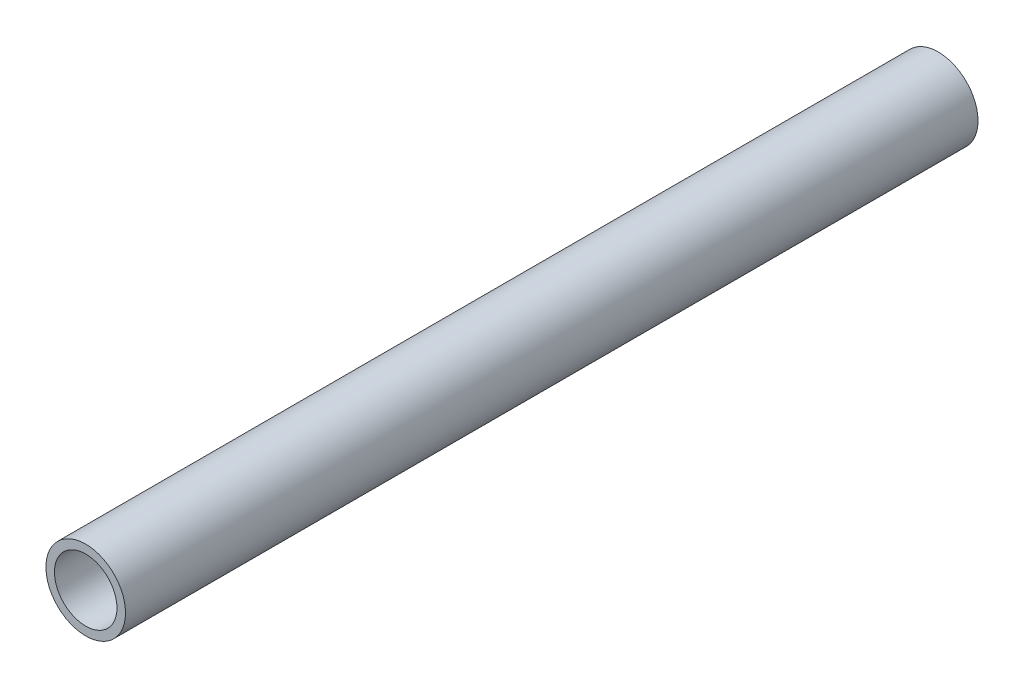
SolidWorks part; units mm, degrees
material "6061-T6 (SS)"
ref_plane "Front Plane" through (0, 0, 0) normal (0, 0, 1) x (1, 0, 0)
ref_plane "Top Plane" through (0, 0, 0) normal (0, 1, 0) x (1, 0, 0)
ref_plane "Right Plane" through (0, 0, 0) normal (1, 0, 0) x (0, 0, -1)
sketch "Sketch1" plane through (0, 0, 0) normal (0, 0, 1) x (1, 0, 0)
  circle A0 centre (0, 0) radius 7
  dimension "D1" = 14
extrude "Boss-Extrude1" add sketch "Sketch1" along normal blind 150
sketch "Sketch2" plane through (0, 0, 150) normal (0, 0, 1) x (1, 0, 0)
  circle A0 centre (0, 0) radius 5.5
  dimension "D1" = 11
extrude "Cut-Extrude1" cut sketch "Sketch2" against normal through all
